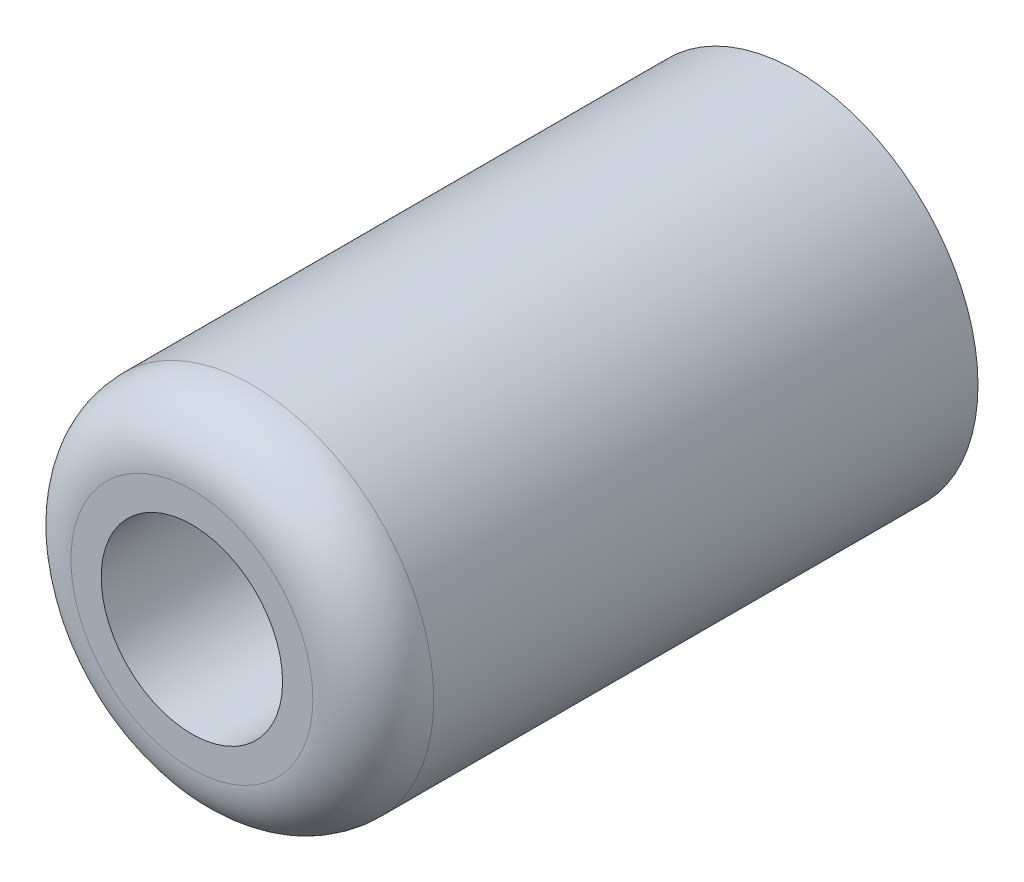
SolidWorks part; units mm, degrees
material "Alliage 1060"
ref_plane "Plan de face" through (0, 0, 0) normal (0, 0, 1) x (1, 0, 0)
ref_plane "Plan de dessus" through (0, 0, 0) normal (0, 1, 0) x (1, 0, 0)
ref_plane "Plan de droite" through (0, 0, 0) normal (1, 0, 0) x (0, 0, -1)
sketch "Esquisse1" plane through (0, 0, 0) normal (0, 0, 1) x (1, 0, 0)
  circle A0 centre (0, 0) radius 6
  circle A1 centre (0, 0) radius 3
  dimension "D1" = 12
  dimension "D2" = 6
extrude "Boss.-Extru.1" add sketch "Esquisse1" along normal blind 20
fillet "Congé1" radius 2 1 edges at (6, 0, 20)
